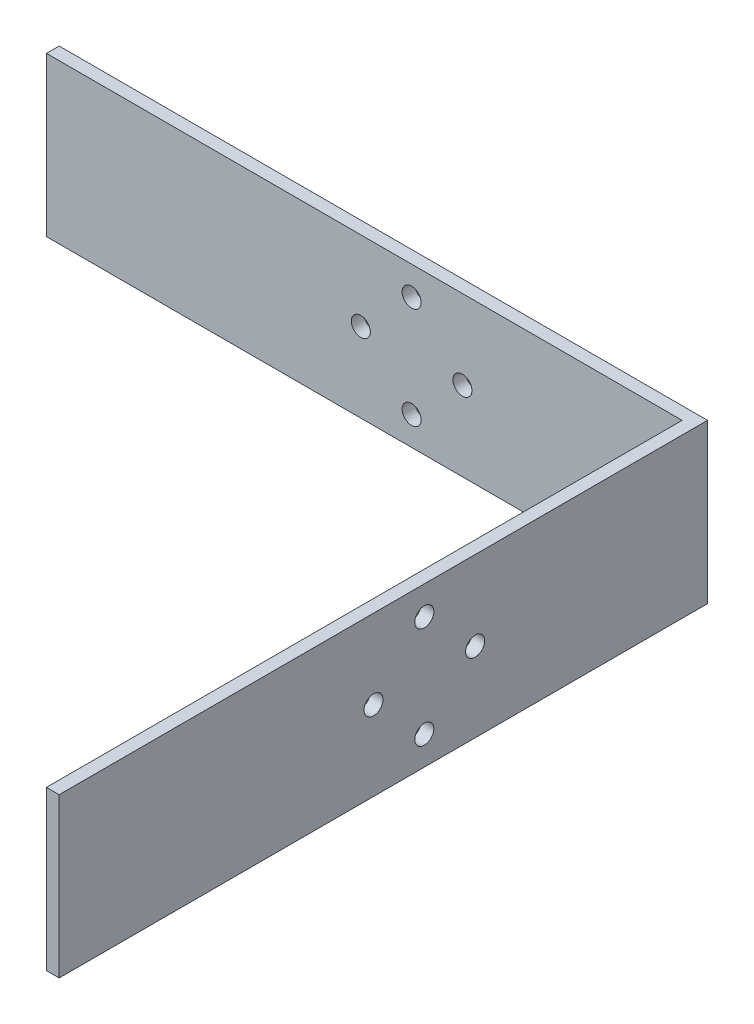
SolidWorks part; units mm, degrees
ref_plane "Front Plane" through (0, 0, 0) normal (0, 0, 1) x (1, 0, 0)
ref_plane "Top Plane" through (0, 0, 0) normal (0, 1, 0) x (1, 0, 0)
ref_plane "Right Plane" through (0, 0, 0) normal (1, 0, 0) x (0, 0, -1)
sketch "Sketch1" plane through (0, 0, 0) normal (0, 1, 0) x (1, 0, 0)
  line L0 (0, 0) -> (102.1, 0)
  line L1 (102.1, -102.1) -> (100.1, -102.1)
  line L2 (100.1, -102.1) -> (100.1, -2)
  line L3 (100.1, -2) -> (0, -2)
  line L4 (0, -2) -> (0, 0)
  line L5 (102.1, 0) -> (102.1, -102.1)
  dimension "D1" = 102.1
  dimension "D3" = 2
  dimension "D4" = 2
extrude "Boss-Extrude1" add sketch "Sketch1" against normal blind 25
sketch "Sketch2" plane through (0, 0, 0) normal (0, 0, -1) x (-1, 0, 0)
  line L0 (-57.5, -4.5) -> (-57.5, -20.5) construction
  line L1 (-65.5, -12.5) -> (-49.5, -12.5) construction
  line L2 (-57.5, -12.5) -> (-57.5, -25) construction
  line L4 (-102.1, -25) -> (0, -25) construction
  line L5 (-57.5, -12.5) -> (-57.5, 0) construction
  line L6 (-102.1, 0) -> (0, 0) construction
  line L8 (-57.5, -12.5) -> (0, -12.5) construction
  line L9 (0, -25) -> (0, 0) construction
  circle A0 centre (-65.5, -12.5) radius 1.5
  circle A1 centre (-57.5, -20.5) radius 1.5
  circle A2 centre (-49.5, -12.5) radius 1.5
  circle A12 centre (-57.5, -4.5) radius 1.5
  point P6 (-57.5, -12.5)
  dimension "D1" = 57.5
  dimension "D2" = 16
  dimension "D3" = 11.3137
  dimension "D6" = 11.3137
  dimension "D8" = 16
sketch "Sketch3" plane through (102.1, 0, 0) normal (1, 0, 0) x (0, 0, -1)
  line L0 (-44.6, -4.5) -> (-44.6, -20.5) construction
  line L1 (-52.6, -12.5) -> (-36.6, -12.5) construction
  line L2 (-44.6, -12.5) -> (-44.6, -25) construction
  line L4 (-44.6, -12.5) -> (-44.6, 0) construction
  line L5 (-44.6, -12.5) -> (-102.1, -12.5) construction
  line L6 (-102.1, -25) -> (-102.1, 0) construction
  circle A0 centre (-52.6, -12.5) radius 1.5
  circle A1 centre (-44.6, -20.5) radius 1.5
  circle A2 centre (-36.6, -12.5) radius 1.5
  circle A12 centre (-44.6, -4.5) radius 1.5
  point P0 (-54.6174, -9.7584)
  point P2 (-44.6, -12.5)
  point P3 (-44.6, -12.5)
  dimension "D8" = 3
  dimension "D9" = 3
  dimension "D2" = 16
  dimension "D6" = 11.3137
  dimension "D7" = 16
  dimension "D10" = 57.5
extrude "Cut-Extrude1" cut sketch "Sketch2" against normal blind 11.3137
extrude "Cut-Extrude2" cut sketch "Sketch3" against normal blind 25 contours A12 | A2 | A0 | A1
